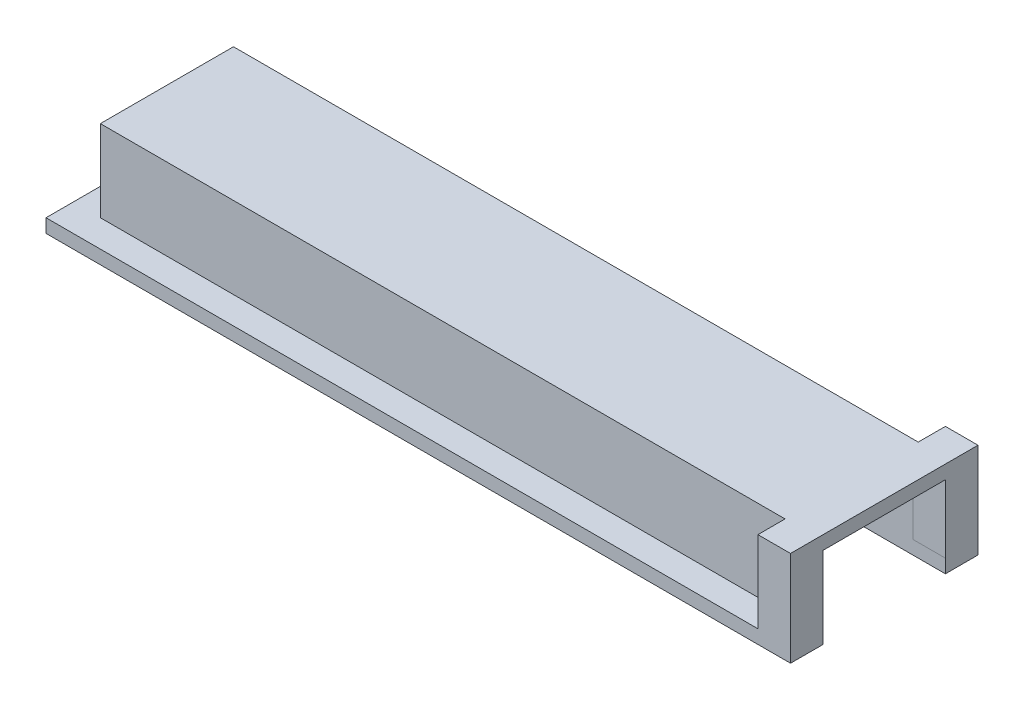
SolidWorks part; units mm, degrees
ref_plane "Front Plane" through (0, 0, 0) normal (0, 0, 1) x (1, 0, 0)
ref_plane "Top Plane" through (0, 0, 0) normal (0, 1, 0) x (1, 0, 0)
ref_plane "Right Plane" through (0, 0, 0) normal (1, 0, 0) x (0, 0, -1)
sketch "Sketch1" plane through (0, 0, 0) normal (0, 1, 0) x (1, 0, 0)
  line L0 (125, -22.5) -> (137, -22.5)
  line L1 (-125, -22.5) -> (125, -22.5)
  line L2 (-125, -22.5) -> (-125, 22.5)
  line L3 (-125, 22.5) -> (125, 22.5)
  line L4 (125, -22.5) -> (125, 22.5)
  line L5 (-125, -22.5) -> (125, 22.5) construction
  line L6 (-125, 22.5) -> (125, -22.5) construction
  line L7 (-137, -34.5) -> (137, -34.5)
  line L8 (-137, -34.5) -> (-137, 34.5)
  line L9 (-137, 34.5) -> (137, 34.5)
  line L10 (137, -34.5) -> (137, 34.5)
  line L11 (-137, -34.5) -> (137, 34.5) construction
  line L12 (-137, 34.5) -> (137, -34.5) construction
  line L13 (125, 22.5) -> (137, 22.5)
  point P0 (0, 0)
  point P6 (0, 0)
  dimension "D1" = 12
  dimension "D2" = 12
  dimension "D3" = 45
  dimension "D4" = 250
extrude "Boss-Extrude1" add sketch "Sketch1" along normal blind 5 contours L3 L13 L10 L9 L8 L7 L0 L1 L2
sketch "Sketch2" plane through (0, 5, 0) normal (0, 1, 0) x (1, 0, 0)
  line L0 (125, 22.4994) -> (137, 22.5)
  line L1 (-125, -22.4994) -> (125, -22.4994)
  line L2 (-125, -22.4994) -> (-125, 22.4994)
  line L3 (-125, 22.4994) -> (125, 22.4994)
  line L4 (125, -22.4994) -> (125, 22.4994)
  line L5 (-125, -22.4994) -> (125, 22.4994) construction
  line L6 (-125, 22.4994) -> (125, -22.4994) construction
  line L7 (-127, -24.4994) -> (127, -24.4994)
  line L8 (-127, -24.4994) -> (-127, 24.4994)
  line L9 (-127, 24.4994) -> (127, 24.4994)
  line L10 (127, -24.4994) -> (127, 24.4994)
  line L11 (-127, -24.4994) -> (127, 24.4994) construction
  line L12 (-127, 24.4994) -> (127, -24.4994) construction
  line L13 (125, 22.4994) -> (125, 34.5)
  line L14 (-137, 34.5) -> (137, 34.5) construction
  line L15 (125, -22.4994) -> (125, -34.5)
  line L16 (-137, -34.5) -> (137, -34.5) construction
  line L17 (125, -22.4994) -> (137, -22.5)
  line L18 (125, -34.5) -> (137, -34.5)
  line L19 (137, -34.5) -> (137, -22.5)
  line L20 (137, 22.5) -> (137, 34.5)
  line L21 (137, 34.5) -> (125, 34.5)
  point P0 (0, 0)
  point P7 (0, 0)
  dimension "D1" = 2
  dimension "D2" = 2
extrude "Boss-Extrude2" add sketch "Sketch2" along normal blind 30 contours L15 L1 L2 L3 L13 L9 L8 L7 | L13 L0 L10 L9 | L17 L15 L7 L10
ref_plane "Plane1" through (137, 0, 34.5) normal (0, -1, 0) x (-1, 0, 0)
sketch "Sketch4" plane through (0, 35, 0) normal (0, 1, 0) x (1, 0, 0)
  line L1 (137, 22.5) -> (-125, 22.5)
  line L2 (137, 22.5) -> (137, -22.5)
  line L3 (137, -22.5) -> (-125, -22.5)
  line L4 (-125, 22.5) -> (-125, -22.5)
extrude "Boss-Extrude3" add sketch "Sketch4" against normal blind 5
